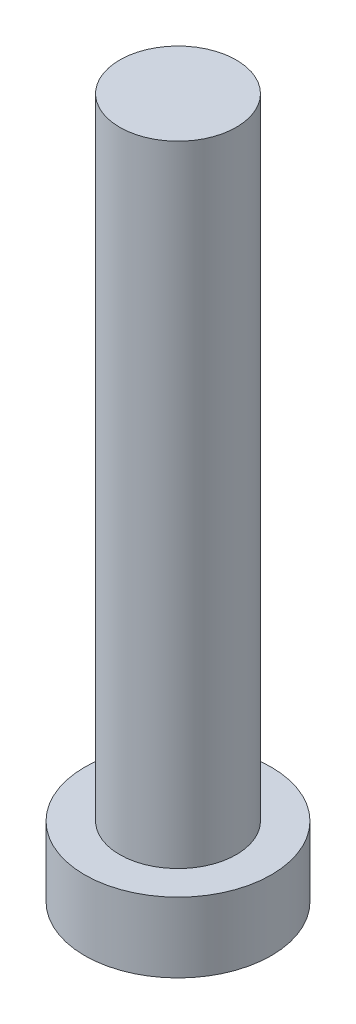
SolidWorks part; units mm, degrees
ref_plane "Front Plane" through (0, 0, 0) normal (0, 0, 1) x (1, 0, 0)
ref_plane "Top Plane" through (0, 0, 0) normal (0, 1, 0) x (1, 0, 0)
ref_plane "Right Plane" through (0, 0, 0) normal (1, 0, 0) x (0, 0, -1)
sketch "Sketch1" plane through (0, 0, 0) normal (0, 1, 0) x (1, 0, 0)
  circle A0 centre (0, 0) radius 2.5
  dimension "D1" = 5
extrude "Boss-Extrude1" add sketch "Sketch1" against normal blind 24 and the other way blind 3.0001
sketch "Sketch2" plane through (0, -24, 0) normal (0, -1, 0) x (-1, 0, 0)
  circle A0 centre (0, 0) radius 4
  dimension "D1" = 8
extrude "Boss-Extrude2" add sketch "Sketch2" along normal blind 3
